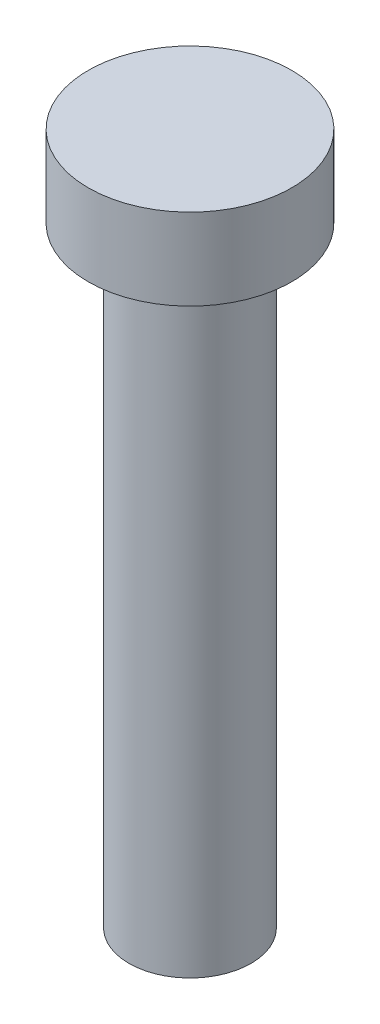
SolidWorks part; units mm, degrees
ref_plane "Plan de face" through (0, 0, 0) normal (0, 0, 1) x (1, 0, 0)
ref_plane "Plan de dessus" through (0, 0, 0) normal (0, 1, 0) x (1, 0, 0)
ref_plane "Plan de droite" through (0, 0, 0) normal (1, 0, 0) x (0, 0, -1)
sketch "Esquisse1" plane through (0, 0, 0) normal (0, 1, 0) x (1, 0, 0)
  circle A0 centre (0, 0) radius 1.5
  dimension "D1" = 3
extrude "Extrusion1" add sketch "Esquisse1" along normal blind 15
sketch "Esquisse2" plane through (0, 15, 0) normal (0, 1, 0) x (1, 0, 0)
  circle A0 centre (0, 0) radius 2.5
  dimension "D1" = 5
extrude "Extrusion2" add sketch "Esquisse2" along normal blind 2
